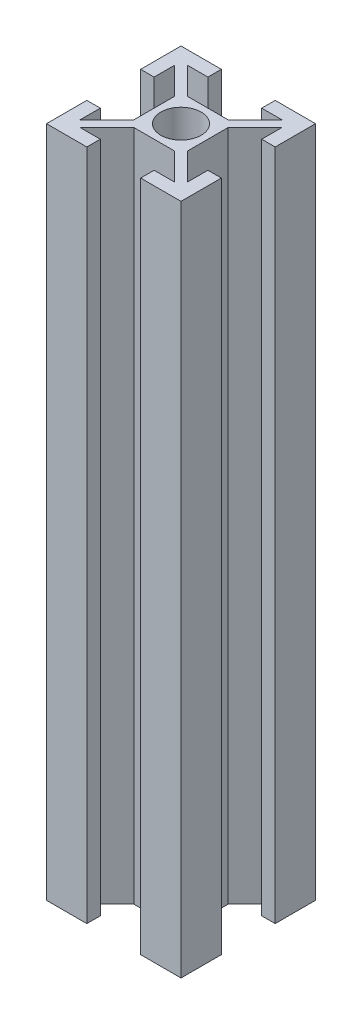
SolidWorks part; units mm, degrees
material "1060 Alloy"
ref_plane "Front Plane" through (0, 0, 0) normal (0, 0, 1) x (1, 0, 0)
ref_plane "Top Plane" through (0, 0, 0) normal (0, 1, 0) x (1, 0, 0)
ref_plane "Right Plane" through (0, 0, 0) normal (1, 0, 0) x (0, 0, -1)
sketch "2020 sketch" plane through (0, 0, 0) normal (0, 1, 0) x (1, 0, 0)
  line L0 (-4, 10) -> (-4, 8)
  line L1 (-10, 10) -> (-4, 10)
  line L2 (-10, 10) -> (-10, 4)
  line L3 (-10, -10) -> (-4, -10)
  line L4 (10, 10) -> (10, 4)
  line L5 (-10, 10) -> (10, -10) construction
  line L6 (-10, -10) -> (10, 10) construction
  line L7 (-4, 8) -> (-7, 8)
  line L8 (-7, 8) -> (-3, 4)
  line L9 (-3, 4) -> (3, 4)
  line L10 (3, 4) -> (7, 8)
  line L11 (7, 8) -> (4, 8)
  line L12 (4, 8) -> (4, 10)
  line L13 (4, 3) -> (4, -3)
  line L14 (8, 7) -> (4, 3)
  line L15 (8, 4) -> (8, 7)
  line L16 (10, 4) -> (8, 4)
  line L17 (8, -4) -> (10, -4)
  line L18 (8, -7) -> (8, -4)
  line L19 (4, -3) -> (8, -7)
  line L20 (3, -4) -> (-3, -4)
  line L21 (7, -8) -> (3, -4)
  line L22 (4, -8) -> (7, -8)
  line L23 (4, -10) -> (4, -8)
  line L24 (-4, -8) -> (-4, -10)
  line L25 (-7, -8) -> (-4, -8)
  line L26 (-3, -4) -> (-7, -8)
  line L27 (-4, -3) -> (-4, 3)
  line L28 (-8, -7) -> (-4, -3)
  line L29 (-8, -4) -> (-8, -7)
  line L30 (-10, -4) -> (-8, -4)
  line L31 (-8, 4) -> (-10, 4)
  line L32 (-8, 7) -> (-8, 4)
  line L33 (-4, 3) -> (-8, 7)
  line L34 (-10, -4) -> (-10, -10)
  line L35 (10, -4) -> (10, -10)
  line L36 (4, 10) -> (10, 10)
  line L37 (4, -10) -> (10, -10)
  circle A0 centre (0, 0) radius 3
  point P0 (0, 0)
  point P14 (4, 9)
  point P42 (0, 0)
  dimension "D9" = 6
  dimension "D1" = 20
  dimension "D2" = 20
  dimension "D3" = 8
  dimension "D4" = 6
  dimension "D5" = 6
  dimension "D6" = 2
  dimension "D7" = 4
  dimension "D8" = 4
extrude "Boss-Extrude1" add sketch "2020 sketch" along normal blind 100 contours A0 | L28 L27 L33 L32 L31 L2 L1 L0 L7 L8 L9 L10 L11 L12 L36 L4 L16 L15 L14 L13 L19 L18 L17 L35 L37 L23 L22 L21 L20 L26 L25 L24 L3 L34 L30 L29
